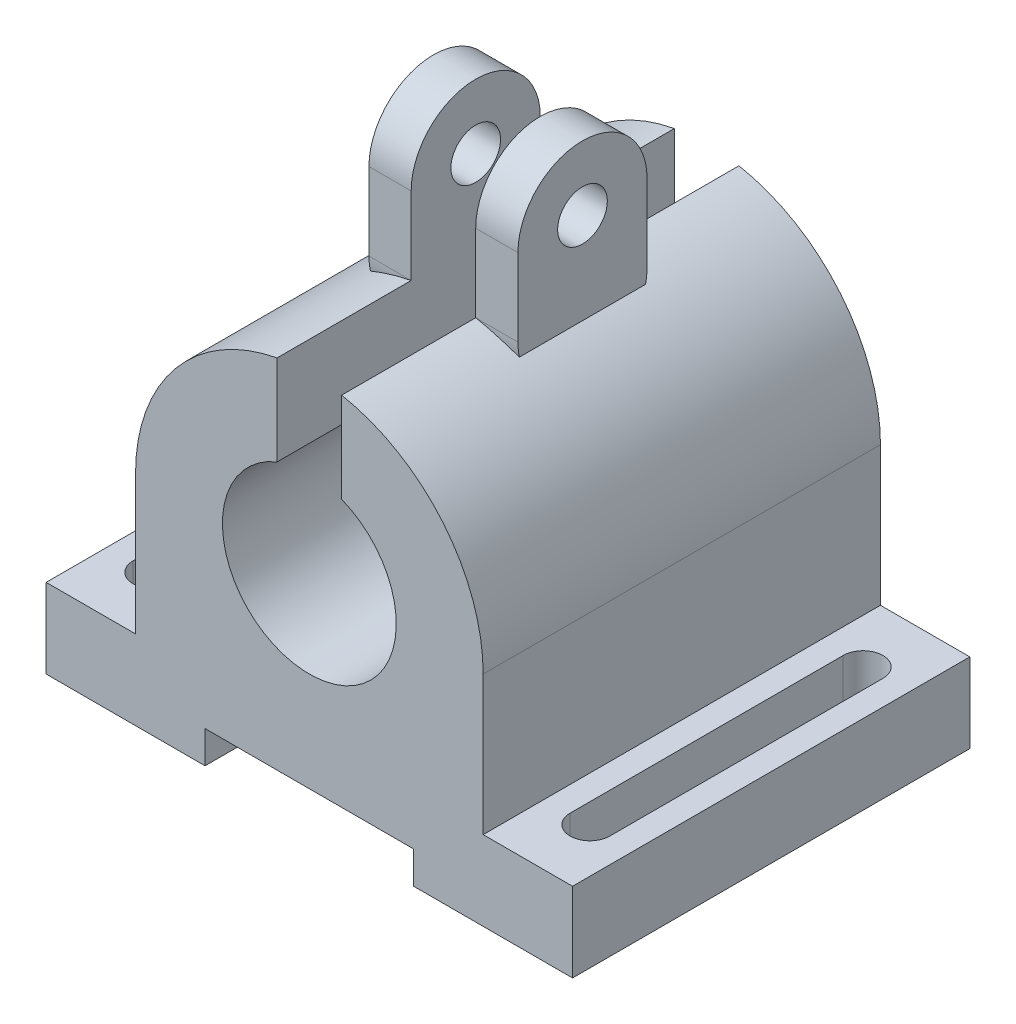
SolidWorks part; units mm, degrees
ref_plane "정면" through (0, 0, 0) normal (0, 0, 1) x (1, 0, 0)
ref_plane "윗면" through (0, 0, 0) normal (0, 1, 0) x (1, 0, 0)
ref_plane "우측면" through (0, 0, 0) normal (1, 0, 0) x (0, 0, -1)
sketch "Sketch2" plane through (0, 0, 0) normal (0, 0, 1) x (1, 0, 0)
  line L0 (0, -37.5021) -> (0, 54.3966) construction
  line L2 (-35, 0) -> (-35, -28)
  line L3 (-21, -37.5) -> (21, -37.5)
  line L4 (35, 0) -> (35, -28)
  line L5 (53, -44) -> (21, -44)
  line L6 (-53, -28) -> (-35, -28)
  line L7 (-53, -28) -> (-53, -44)
  line L8 (-53, -44) -> (-21, -44)
  line L9 (-21, -37.5) -> (-21, -44)
  line L10 (21, -37.5) -> (21, -44)
  line L11 (53, -28) -> (35, -28)
  line L12 (53, -28) -> (53, -44)
  line L14 (-6.5, 16.2481) -> (-6.5, 34.3911)
  line L16 (6.5, 16.2481) -> (6.5, 34.3911)
  line L23 (15, 9.0139) -> (15, 8.8473)
  line L24 (-15, 9.0139) -> (-15, 8.8473)
  arc A0 (35, 0) -> (6.5, 34.3911) centre (0, 0) ccw
  arc A1 (-6.5, 16.2481) -> (6.5, 16.2481) centre (0, 0) ccw
  arc A2 (-6.5, 34.3911) -> (-35, 0) centre (0, 0) ccw
  point P21 (0, 11.3249)
  dimension "D5" = 35
  dimension "D6" = 35
  dimension "D1" = 44
  dimension "D2" = 42
  dimension "D3" = 6.5
  dimension "D4" = 16
  dimension "D7" = 13
  dimension "D8" = 106
extrude "Boss-Extrude1" add sketch "Sketch2" along normal blind 80 contours L3 L0 A1 L14 A2 L2 L6 L7 L8 L9 | L0 L3 L10 L5 L12 L11 L4 A0 L16 A1
sketch "Sketch3" plane through (-6.5, 0, 0) normal (1, 0, 0) x (0, 0, -1)
  line L0 (-40, 34.3911) -> (-40, 50) construction
  line L1 (-80, 34.3911) -> (0, 34.3911) construction
  line L2 (-53, 34.3911) -> (-53, 50)
  line L3 (-27, 34.3911) -> (-27, 50)
  line L4 (-80, -44) -> (0, -44) construction
  arc A0 (-53, 34.3911) -> (-27, 34.3911) centre (-40, 34.3911) ccw
  arc A1 (-27, 50) -> (-53, 50) centre (-40, 50) ccw
  point P4 (-40, 42.1956)
  dimension "D1" = 13
  dimension "D2" = 94
sketch "Sketch5" plane through (6.5, 0, 0) normal (-1, 0, 0) x (0, 0, 1)
  line L0 (40, 34.3911) -> (40, 50) construction
  line L1 (27, 34.3911) -> (27, 50)
  line L2 (53, 34.3911) -> (53, 50)
  arc A0 (27, 34.3911) -> (53, 34.3911) centre (40, 34.3911) ccw
  arc A1 (53, 50) -> (27, 50) centre (40, 50) ccw
  point P4 (40, 42.1956)
  dimension "D1" = 13
extrude "Boss-Extrude3" add sketch "Sketch5" against normal blind 8.5
extrude "Boss-Extrude4" add sketch "Sketch3" against normal blind 8.5
hole_wizard "Ø10.0 (10) Diameter Hole1" positions "3DSketch1" profile "Sketch6" hole size "Ø10.0" standard "Ansi Metric" end condition through all
sketch3d "3DSketch1"
  line L0 (15, 50, 40) -> (6.5, 50, 40) construction
  point P0 (15, 50, 40)
sketch "Sketch6" plane through (15, 50, 40) normal (0, 1, 0) x (0, 0, -1)
  line L0 (0, 0) -> (0, 68)
  line L1 (0, 68) -> (5, 68)
  line L2 (5, 68) -> (5, 0)
  line L5 (5, 0) -> (0, 0)
  line L11 (0, -6.35) -> (0, 107.95) construction
  dimension "관통 구멍 지름" = 10
  dimension "관통 구멍 깊이" = 68
sketch "Sketch7" plane through (0, -28, 0) normal (0, 1, 0) x (1, 0, 0)
  line L0 (-44, -12.5) -> (-44, -67.5) construction
  line L1 (-40, -12.5) -> (-40, -67.5)
  line L2 (-48, -12.5) -> (-48, -67.5)
  line L4 (0, 0) -> (0, -80) construction
  line L5 (44, -12.5) -> (44, -67.5) construction
  line L6 (40, -12.5) -> (40, -67.5)
  line L7 (48, -12.5) -> (48, -67.5)
  line L8 (-17.5, -80) -> (17.5, -80) construction
  arc A0 (-40, -12.5) -> (-48, -12.5) centre (-44, -12.5) ccw
  arc A1 (-48, -67.5) -> (-40, -67.5) centre (-44, -67.5) ccw
  arc A2 (40, -12.5) -> (48, -12.5) centre (44, -12.5) cw
  arc A3 (48, -67.5) -> (40, -67.5) centre (44, -67.5) cw
  point P2 (-44, -40)
  point P12 (44, -40)
  point P17 (0, -80)
  point P20 (0, 0)
  point P21 (0, -40)
  point P22 (0, 0)
  dimension "D1" = 4
  dimension "D2" = 88
  dimension "D3" = 55
extrude "Cut-Extrude1" cut sketch "Sketch7" against normal through all
